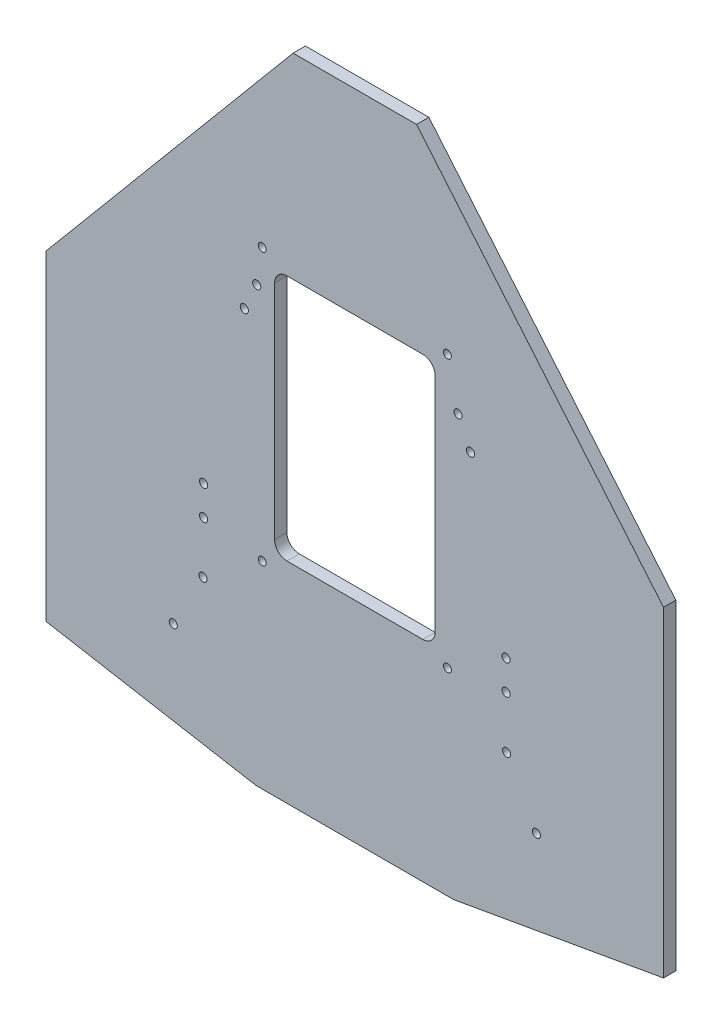
SolidWorks part; units mm, degrees
ref_plane "Front" through (0, 0, 0) normal (0, 0, 1) x (1, 0, 0)
ref_plane "Top" through (0, 0, 0) normal (0, 1, 0) x (1, 0, 0)
ref_plane "Right" through (0, 0, 0) normal (1, 0, 0) x (0, 0, -1)
sketch "Эскиз1" plane through (0, 0, 0) normal (0, 0, 1) x (1, 0, 0)
  line L0 (-35, -48) -> (-35, -58)
  line L1 (-35, -58) -> (50, -73)
  line L2 (50, -73) -> (130, -73)
  line L3 (130, -73) -> (215, -58)
  line L4 (215, -58) -> (215, -48)
  line L8 (215, 62) -> (180, 62) construction
  line L9 (215, 62) -> (215, 72)
  line L11 (-35, 72) -> (-35, 62)
  line L15 (122.5, 112) -> (122.5, 69.7084) construction
  line L16 (122.5, 112) -> (122.5, 12)
  line L17 (122.5, 112) -> (57.5, 112)
  line L18 (57.5, 112) -> (57.5, 12)
  line L19 (122.5, 12) -> (57.5, 12)
  line L20 (122.5, 112) -> (57.5, 12) construction
  line L21 (57.5, 112) -> (122.5, 12) construction
  line L22 (90, -73) -> (90, 12) construction
  line L26 (90, -73) -> (90, 271.3968) construction
  line L29 (215, 72) -> (115, 191.3603)
  line L30 (115, 191.3603) -> (65, 191.3603)
  line L31 (65, 191.3603) -> (-35, 72)
  line L33 (215, -48) -> (215, 62)
  line L34 (-35, -48) -> (-35, 62)
  dimension "D1" = 65
  dimension "D2" = 100
extrude "Бобышка-Вытянуть1" add sketch "Эскиз1" along normal blind 5
sketch "Эскиз2" plane through (0, 0, 5) normal (0, 0, 1) x (1, 0, 0)
  line L0 (57.5, 12) -> (57.5, 7) construction
  line L2 (57.5, 7) -> (52.5, 7) construction
  circle A0 centre (52.5, 7) radius 1.6
  dimension "D1" = 5
  dimension "D2" = 5
extrude "Вырез-Вытянуть1" cut sketch "Эскиз2" against normal blind 5
pattern_linear "Линейный массив1" count 2 spacing 75 along (1, 0, 0) count 2 spacing 110 along (0, 1, 0) of "Вырез-Вытянуть1"
fillet "Скругление1" radius 5 4 edges at (122.5, 12, 2.5) (57.5, 12, 2.5) (57.5, 112, 2.5) (122.5, 112, 2.5)
sketch "Эскиз4" plane through (0, 0, 0) normal (0, 0, -1) x (-1, 0, 0)
  circle A0 centre (-16.4711, -33) radius 1.65 construction
  circle A1 centre (-28.5289, -10.64) radius 1.65 construction
  circle A2 centre (-28.75, 22.36) radius 1.65 construction
  circle A3 centre (-28.75, 10.36) radius 1.65 construction
  circle A4 centre (-45.2456, 91.8843) radius 1.65 construction
  circle A5 centre (-50.2743, 102.7798) radius 1.65 construction
  circle A6 centre (-131.8211, 98.2399) radius 1.65 construction
  circle A7 centre (-136.8498, 87.3444) radius 1.65 construction
  circle A8 centre (-151.4711, -10.64) radius 1.65 construction
  circle A9 centre (-163.5289, -33) radius 1.65 construction
  circle A10 centre (-16.4711, -33) radius 1.65
  circle A11 centre (-28.5289, -10.64) radius 1.65
  circle A12 centre (-28.75, 22.36) radius 1.65
  circle A13 centre (-28.75, 10.36) radius 1.65
  circle A14 centre (-45.2456, 91.8843) radius 1.65
  circle A15 centre (-50.2743, 102.7798) radius 1.65
  circle A16 centre (-131.8211, 98.2399) radius 1.65
  circle A17 centre (-136.8498, 87.3444) radius 1.65
  circle A18 centre (-151.4711, -10.64) radius 1.65
  circle A19 centre (-163.5289, -33) radius 1.65
  circle A20 centre (-151.25, 22.36) radius 1.65 construction
  circle A21 centre (-151.25, 10.36) radius 1.65 construction
  circle A22 centre (-151.25, 22.36) radius 1.65
  circle A23 centre (-151.25, 10.36) radius 1.65
extrude "Вырез-Вытянуть2" cut sketch "Эскиз4" against normal blind 31
